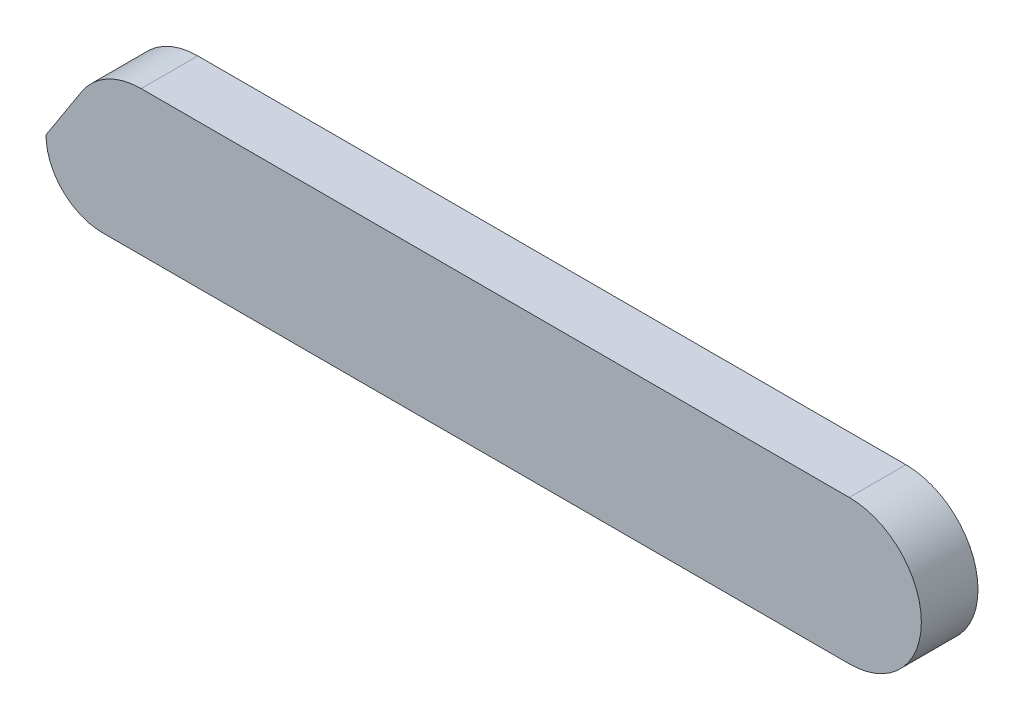
SolidWorks part; units mm, degrees
ref_plane "Front Plane" through (0, 0, 0) normal (0, 0, 1) x (1, 0, 0)
ref_plane "Top Plane" through (0, 0, 0) normal (0, 1, 0) x (1, 0, 0)
ref_plane "Right Plane" through (0, 0, 0) normal (1, 0, 0) x (0, 0, -1)
sketch "Sketch2" plane through (0, 0, 0) normal (0, 0, 1) x (1, 0, 0)
  line L0 (-50.6838, 15.3768) -> (49.3162, 15.3768)
  line L1 (49.3162, -4.9831) -> (-56.1288, -4.9831)
  line L2 (-64.1195, 3.0076) -> (-59.0834, 10.8032)
  arc A0 (49.3162, 15.3768) -> (49.3162, -4.9831) centre (49.3162, 5.1968) cw
  arc A1 (-56.1288, -4.9831) -> (-64.1195, 3.0076) centre (-56.1288, 3.0076) cw
  arc A2 (-50.6838, 15.3768) -> (-59.0834, 10.8032) centre (-50.6838, 5.3768) ccw
  dimension "D1" = 10
  dimension "D5" = 49.3162
  dimension "D6" = 12.3692
  dimension "D8" = 56.1288
  dimension "D2" = 15.3768
  dimension "D3" = 100
  dimension "D4" = 20.3599
  dimension "D7" = 57.137
extrude "Boss-Extrude1" add sketch "Sketch2" along normal blind 8
sketch "Sketch4" plane through (0, -4.9831, 0) normal (0, -1, 0) x (1, 0, 0)
  line L0 (-56.1288, 8) -> (-56.1288, 0) construction
  line L2 (-56.1288, 0) -> (49.3162, 0) construction
  circle A0 centre (-53.2798, 4) radius 2.55
  dimension "D2" = 5.1
  dimension "D1" = 2.849
  dimension "3.5" = 4
extrude "Cut-Extrude1" cut sketch "Sketch4" against normal blind 7
